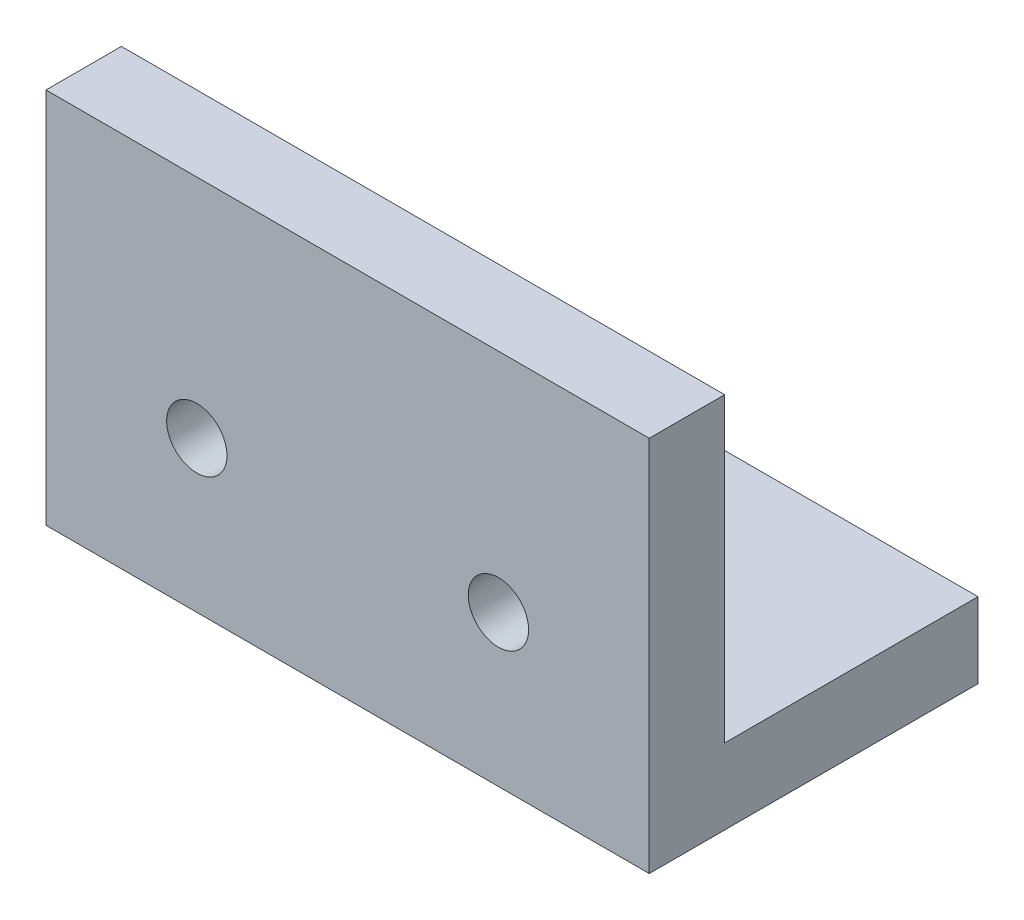
SolidWorks part; units mm, degrees
ref_plane "Front Plane" through (0, 0, 0) normal (0, 0, 1) x (1, 0, 0)
ref_plane "Top Plane" through (0, 0, 0) normal (0, 1, 0) x (1, 0, 0)
ref_plane "Right Plane" through (0, 0, 0) normal (1, 0, 0) x (0, 0, -1)
sketch "Sketch1" plane through (0, 0, 0) normal (1, 0, 0) x (0, 0, -1)
  line L0 (0, 0) -> (0, 12.7)
  line L1 (0, 0) -> (10.668, 0)
  line L2 (-3.175, -3.175) -> (10.668, -3.175)
  line L3 (-3.175, -3.175) -> (-3.175, 12.7)
  line L4 (-3.175, 12.7) -> (0, 12.7)
  line L5 (10.668, 0) -> (10.668, -3.175)
  dimension "D1" = 12.7
  dimension "D2" = 10.668
  dimension "D3" = 3.175
extrude "Boss-Extrude1" add sketch "Sketch1" along normal blind 25.4
sketch "Sketch2" plane through (0, 0, 3.175) normal (0, 0, 1) x (1, 0, 0)
  line L0 (25.4, 12.7) -> (25.4, -3.175) construction
  line L1 (25.4, 0) -> (0, 0) construction
  line L2 (25.4, 0) -> (0, 0) construction
  line L3 (0, 12.7) -> (0, -3.175) construction
  circle A0 centre (6.35, 3.175) radius 1.27
  circle A1 centre (19.05, 3.175) radius 1.27
  dimension "D2" = 2.54
  dimension "D4" = 2.54
  dimension "D1" = 6.35
  dimension "D3" = 3.175
  dimension "D5" = 3.175
  dimension "D6" = 6.35
extrude "Cut-Extrude1" cut sketch "Sketch2" against normal blind 25.4
